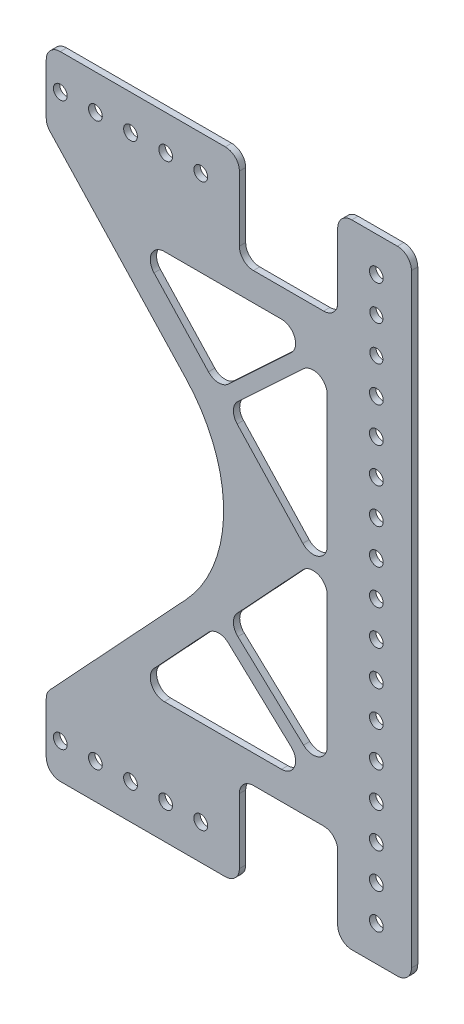
SolidWorks part; units mm, degrees
ref_plane "Front Plane" through (0, 0, 0) normal (0, 0, 1) x (1, 0, 0)
ref_plane "Top Plane" through (0, 0, 0) normal (0, 1, 0) x (1, 0, 0)
ref_plane "Right Plane" through (0, 0, 0) normal (1, 0, 0) x (0, 0, -1)
sketch "Sketch1" plane through (0, 0, 0) normal (0, 0, 1) x (1, 0, 0)
  line L11 (65.4076, 898.4977) -> (48.8976, 898.4977)
  line L12 (43.8176, 893.4177) -> (43.8176, 869.9227)
  line L13 (38.7376, 864.8427) -> (13.3376, 864.8427)
  line L14 (8.2576, 869.9227) -> (8.2576, 893.4177)
  line L15 (3.1776, 898.4977) -> (-56.5124, 898.4977)
  line L16 (-60.2304, 871.6349) -> (-11.0513, 818.8143)
  line L17 (70.4876, 893.4177) -> (70.4876, 784.1977)
  line L18 (-61.5924, 875.0965) -> (-61.5924, 893.4177)
  line L20 (-22.6122, 846.1411) -> (-2.9253, 824.9965)
  line L21 (40.0076, 791.7957) -> (40.0076, 839.4169)
  line L22 (23.5028, 854.6827) -> (-18.8942, 854.6827)
  line L23 (70.4876, 674.9777) -> (70.4876, 784.1977)
  line L24 (65.4076, 669.8977) -> (48.8976, 669.8977)
  line L25 (43.8176, 674.9777) -> (43.8176, 698.4727)
  line L26 (38.7376, 703.5527) -> (13.3376, 703.5527)
  line L27 (8.2576, 698.4727) -> (8.2576, 674.9777)
  line L28 (-60.2304, 696.7606) -> (-11.0513, 749.5812)
  line L29 (3.1776, 669.8977) -> (-56.5124, 669.8977)
  line L30 (-61.5924, 693.2989) -> (-61.5924, 674.9777)
  line L31 (26.9645, 845.8848) -> (4.2543, 824.7402)
  line L32 (7.4596, 754.5529) -> (31.2096, 780.0614)
  line L33 (31.4659, 843.1349) -> (7.716, 821.0222)
  line L34 (7.4596, 813.8426) -> (31.2096, 788.3341)
  line L35 (40.0076, 776.5997) -> (40.0076, 728.9785)
  line L36 (31.4659, 725.2606) -> (7.716, 747.3732)
  line L37 (26.9645, 722.5107) -> (4.2543, 743.6552)
  line L38 (-22.6122, 722.2544) -> (-2.9253, 743.3989)
  line L39 (23.5028, 713.7127) -> (-18.8942, 713.7127)
  arc A1 (65.4076, 898.4977) -> (70.4876, 893.4177) centre (65.4076, 893.4177) cw
  arc A2 (48.8976, 898.4977) -> (43.8176, 893.4177) centre (48.8976, 893.4177) ccw
  arc A3 (43.8176, 869.9227) -> (38.7376, 864.8427) centre (38.7376, 869.9227) cw
  arc A4 (13.3376, 864.8427) -> (8.2576, 869.9227) centre (13.3376, 869.9227) cw
  arc A5 (8.2576, 893.4177) -> (3.1776, 898.4977) centre (3.1776, 893.4177) ccw
  arc A6 (-56.5124, 898.4977) -> (-61.5924, 893.4177) centre (-56.5124, 893.4177) ccw
  circle A7 centre (-31.1124, 885.7977) radius 2.4892
  circle A8 centre (-18.4124, 885.7977) radius 2.4892
  circle A9 centre (-5.7124, 885.7977) radius 2.4892
  circle A11 centre (57.7876, 860.3977) radius 2.3719
  circle A12 centre (57.7876, 847.6977) radius 2.4892
  circle A13 centre (57.7876, 834.9977) radius 2.4892
  circle A14 centre (57.7876, 822.2977) radius 2.4892
  circle A15 centre (57.7876, 809.5977) radius 2.4892
  arc A16 (-60.2304, 871.6349) -> (-61.5924, 875.0965) centre (-56.5124, 875.0965) cw
  arc A17 (31.2096, 788.3341) -> (40.0076, 791.7957) centre (34.9276, 791.7957) ccw
  arc A18 (-22.6122, 846.1411) -> (-18.8942, 854.6827) centre (-18.8942, 849.6027) cw
  arc A19 (65.4076, 669.8977) -> (70.4876, 674.9777) centre (65.4076, 674.9777) ccw
  arc A20 (48.8976, 669.8977) -> (43.8176, 674.9777) centre (48.8976, 674.9777) cw
  arc A21 (43.8176, 698.4727) -> (38.7376, 703.5527) centre (38.7376, 698.4727) ccw
  arc A22 (13.3376, 703.5527) -> (8.2576, 698.4727) centre (13.3376, 698.4727) ccw
  arc A23 (8.2576, 674.9777) -> (3.1776, 669.8977) centre (3.1776, 674.9777) cw
  circle A24 centre (-5.7124, 682.5977) radius 2.4892
  circle A25 centre (-18.4124, 682.5977) radius 2.4892
  circle A26 centre (-31.1124, 682.5977) radius 2.4892
  arc A27 (-60.2304, 696.7606) -> (-61.5924, 693.2989) centre (-56.5124, 693.2989) ccw
  arc A28 (-56.5124, 669.8977) -> (-61.5924, 674.9777) centre (-56.5124, 674.9777) cw
  circle A29 centre (57.7876, 733.3977) radius 2.4892
  circle A30 centre (57.7876, 720.6977) radius 2.4892
  circle A31 centre (57.7876, 707.9977) radius 2.4892
  circle A32 centre (57.7876, 682.5977) radius 2.4892
  circle A33 centre (57.7876, 885.7977) radius 2.4892
  arc A34 (-11.0513, 818.8143) -> (-11.0513, 749.5812) centre (-48.231, 784.1977) cw
  circle A35 centre (57.7876, 771.4977) radius 2.4892
  circle A36 centre (57.7876, 758.7977) radius 2.4892
  circle A37 centre (57.7876, 746.0977) radius 2.4892
  circle A38 centre (-56.5124, 885.7977) radius 2.4892
  circle A39 centre (-43.8124, 885.7977) radius 2.4892
  circle A40 centre (-43.8124, 682.5977) radius 2.4892
  circle A41 centre (-56.5124, 682.5977) radius 2.4892
  arc A42 (7.716, 821.0222) -> (7.4596, 813.8426) centre (11.1776, 817.3043) ccw
  arc A43 (31.4659, 843.1349) -> (40.0076, 839.4169) centre (34.9276, 839.4169) cw
  arc A44 (26.9645, 845.8848) -> (23.5028, 854.6827) centre (23.5028, 849.6027) ccw
  arc A45 (4.2543, 824.7402) -> (-2.9253, 824.9965) centre (0.7927, 828.4582) cw
  arc A46 (31.2096, 780.0614) -> (40.0076, 776.5997) centre (34.9276, 776.5997) cw
  arc A47 (7.716, 747.3732) -> (7.4596, 754.5529) centre (11.1776, 751.0912) cw
  arc A48 (31.4659, 725.2606) -> (40.0076, 728.9785) centre (34.9276, 728.9785) ccw
  arc A49 (26.9645, 722.5107) -> (23.5028, 713.7127) centre (23.5028, 718.7927) cw
  arc A50 (4.2543, 743.6552) -> (-2.9253, 743.3989) centre (0.7927, 739.9373) ccw
  arc A51 (-22.6122, 722.2544) -> (-18.8942, 713.7127) centre (-18.8942, 718.7927) ccw
  circle A52 centre (57.7876, 796.8977) radius 2.4892
  circle A53 centre (57.7876, 784.1977) radius 2.4892
  circle A54 centre (57.7876, 873.0977) radius 2.3719
  circle A55 centre (57.7876, 695.2977) radius 2.4892
  point P14 (70.4876, 784.1977)
  point P17 (45.0876, 784.1977)
  dimension "D1" = 10.16
  dimension "D3" = 5.08
  dimension "D4" = 50.8
  dimension "D5" = 5.08
  dimension "D6" = 5.08
  dimension "D8" = 5.08
  dimension "D11" = 12.7
  dimension "D12" = 12.7
  dimension "D2" = 10.16
  dimension "D7" = 5.08
  dimension "D9" = 3
  dimension "D10" = 2
extrude "Boss-Extrude2" add sketch "Sketch1" along normal blind 2.286 contours L16 A34 L28 A27 L30 A28 L29 A23 L27 A22 L26 A21 L25 A20 L24 A19 L23 L17 A1 L11 A2 L12 A3 L13 A4 L14 A5 L15 A6 L18 A16 A55 A54 A53 A52 A51 L38 A50 L37 A49 L39 A48 L36 A47 L32
